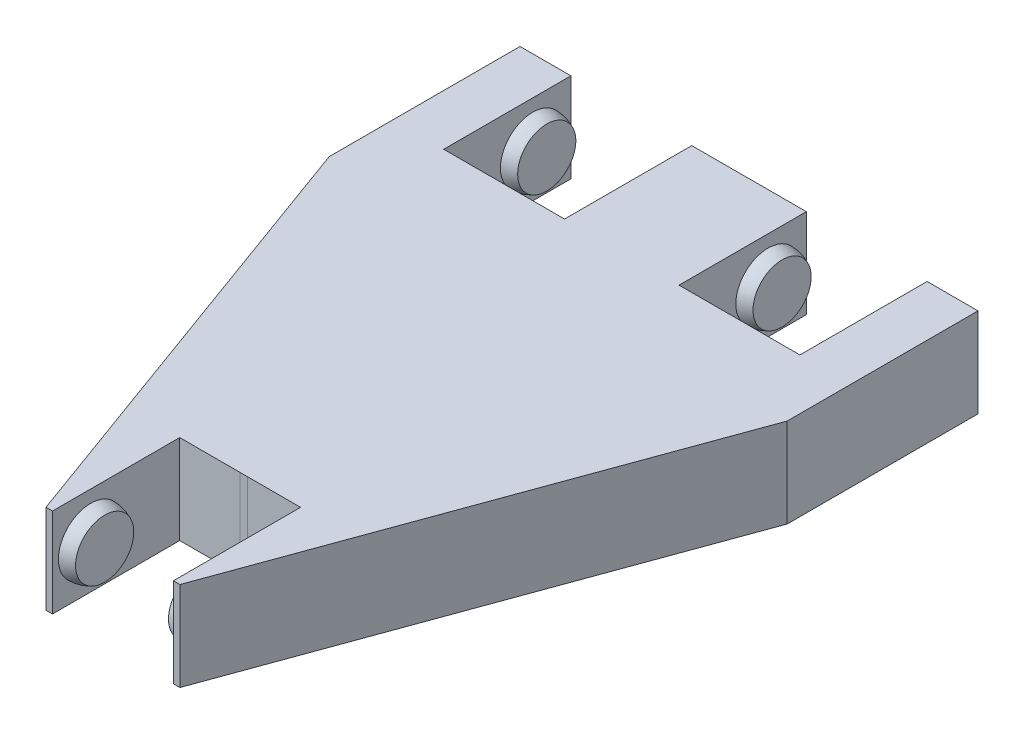
SolidWorks part; units mm, degrees
material "PBT General Purpose"
ref_plane "Front Plane" through (0, 0, 0) normal (0, 0, 1) x (1, 0, 0)
ref_plane "Top Plane" through (0, 0, 0) normal (0, 1, 0) x (1, 0, 0)
ref_plane "Right Plane" through (0, 0, 0) normal (1, 0, 0) x (0, 0, -1)
sketch "Sketch1" plane through (0, 0, 0) normal (0, 1, 0) x (1, 0, 0)
  line L1 (-36, 50) -> (36, 50)
  line L2 (-36, 50) -> (-36, -50)
  line L3 (-36, -50) -> (36, -50)
  line L4 (36, 50) -> (36, -50)
  line L5 (-36, 50) -> (36, -50) construction
  line L6 (-36, -50) -> (36, 50) construction
  line L7 (-28, 50) -> (-9, 50)
  line L8 (-28, 50) -> (-28, 30)
  line L9 (-28, 30) -> (-9, 30)
  line L10 (-9, 50) -> (-9, 30)
  line L11 (9, 50) -> (28, 50)
  line L12 (9, 50) -> (9, 30)
  line L13 (9, 30) -> (28, 30)
  line L14 (28, 50) -> (28, 30)
  line L15 (-9.5, -30) -> (9.5, -30)
  line L16 (-9.5, -30) -> (-9.5, -50)
  line L17 (-9.5, -50) -> (9.5, -50)
  line L18 (9.5, -30) -> (9.5, -50)
  point P0 (0, 0)
  point P14 (-9.5, -40)
  dimension "D1" = 100
  dimension "D2" = 72
  dimension "D3" = 20
  dimension "D4" = 19
  dimension "D5" = 19
  dimension "D6" = 20
  dimension "D7" = 18
  dimension "D8" = 8
  dimension "D9" = 19
  dimension "D10" = 20
  dimension "D11" = 26.5
extrude "Boss-Extrude1" add sketch "Sketch1" along normal blind 14.0278 contours L15 L18 L3 L4 L1 L14 L13 L12 L10 L9 L8 L2 L16
chamfer "Chamfer1" distance 70 angle 20 1 edges at (36, 7.0139, 50)
chamfer "Chamfer2" distance 70 angle 20 1 edges at (-36, 7.0139, 50)
sketch "Sketch2" plane through (-9.5, 0, 0) normal (1, 0, 0) x (0, 0, -1)
  line L2 (-30, 0) -> (-50, 0) construction
  line L3 (-50, 14.0278) -> (-50, 0) construction
  circle A0 centre (-44, 7) radius 5.075
  dimension "D3" = 10.15
  dimension "D1" = 7
  dimension "D2" = 6
sketch "Sketch4" plane through (-9.5, 0, 0) normal (1, 0, 0) x (0, 0, -1)
  line L0 (-49.075, 7) -> (-38.925, 7)
  arc A0 (-38.925, 7) -> (-49.075, 7) centre (-44, 7) ccw
  circle A1 centre (-44, 7) radius 5.075 construction
revolve "Revolve1" add sketch "Sketch4" angle 180 about L0
sketch "Sketch5" plane through (0, 0, 50) normal (0, 0, 1) x (1, 0, 0)
  line L0 (-9.5, 1.925) -> (-9.5, 12.075) construction
  line L1 (-7.3, 13.519) -> (-3.9276, 13.519)
  line L2 (-7.3, 13.519) -> (-7.3, 1.5195)
  line L3 (-7.3, 1.5195) -> (-3.9276, 1.5195)
  line L4 (-3.9276, 13.519) -> (-3.9276, 1.5195)
  dimension "D1" = 2.2
extrude "Cut-Extrude1" cut sketch "Sketch5" against normal blind 12
sketch "Sketch8" plane through (-28, 0, 0) normal (1, 0, 0) x (0, 0, -1)
  line L0 (38.925, 7) -> (49.075, 7)
  line L1 (50, 14.0278) -> (50, 0) construction
  line L2 (50, 0) -> (30, 0) construction
  arc A0 (38.925, 7) -> (49.075, 7) centre (44, 7) cw
  dimension "D1" = 5.075
  dimension "D2" = 6
  dimension "D3" = 7
revolve "Revolve2" add sketch "Sketch8" angle 180 about L0
sketch "Sketch10" plane through (0, 0, -50) normal (0, 0, -1) x (-1, 0, 0)
  line L0 (9, 14.0278) -> (-9, 14.0278) construction
  line L1 (0, 14.0278) -> (-9, 14.0278)
  line L2 (0, 14.0278) -> (0, 0)
  line L3 (0, 0) -> (-9, 0)
  line L4 (-9, 14.0278) -> (-9, 0)
extrude "Boss-Extrude2" add sketch "Sketch10" along normal blind 0.01
mirror "Mirror2" about plane through (0, 14.0278, -50.01) normal (1, 0, 0) of "Revolve2"
sketch "Sketch11" plane through (0, 0, 30) normal (0, 0, 1) x (1, 0, 0)
  line L0 (-9.5, 14.0278) -> (9.5, 14.0278) construction
  line L1 (0, 0) -> (1.1735, 0)
  line L2 (0, 0) -> (0, 14.0278)
  line L3 (0, 14.0278) -> (1.1735, 14.0278)
  line L4 (1.1735, 0) -> (1.1735, 14.0278)
extrude "Boss-Extrude3" add sketch "Sketch11" along normal blind 0.01
mirror "Mirror4" about plane through (0, 0, 30.01) normal (1, 0, 0) of "Revolve1"
sketch "Sketch12" plane through (0, 0, 50) normal (0, 0, 1) x (1, 0, 0)
  line L0 (9.5, 14.0278) -> (9.5, 0) construction
  line L1 (3.7027, 12.7379) -> (7.3, 12.7379)
  line L2 (3.7027, 12.7379) -> (3.7027, 1.3925)
  line L3 (3.7027, 1.3925) -> (7.3, 1.3925)
  line L4 (7.3, 12.7379) -> (7.3, 1.3925)
  dimension "D1" = 2.2
extrude "Cut-Extrude2" cut sketch "Sketch12" against normal blind 12
sketch "Sketch13" plane through (0, 0, -30) normal (0, 0, -1) x (-1, 0, 0)
  line L0 (-9, 0) -> (-28, 0) construction
  line L1 (-18.5, 0) -> (-16.6932, 0)
  line L2 (-18.5, 0) -> (-18.5, 14.0278)
  line L3 (-18.5, 14.0278) -> (-16.6932, 14.0278)
  line L4 (-16.6932, 0) -> (-16.6932, 14.0278)
  line L5 (-9, 14.0278) -> (-28, 14.0278) construction
extrude "Boss-Extrude4" add sketch "Sketch13" along normal blind 0.01
mirror "Mirror5" about plane through (18.5, 0, -30.01) normal (-1, 0, 0) of "Mirror2"
mirror "Mirror6" about plane through (0, 14.0278, -50.01) normal (1, 0, 0) of "Mirror5"
sketch "Sketch14" plane through (0, 0, -50) normal (0, 0, -1) x (-1, 0, 0)
  line L0 (-9, 12.075) -> (-9, 1.925) construction
  line L1 (-25.8, 12.7501) -> (-11.2, 12.7501)
  line L2 (-25.8, 12.7501) -> (-25.8, 1.2155)
  line L3 (-25.8, 1.2155) -> (-11.2, 1.2155)
  line L4 (-11.2, 12.7501) -> (-11.2, 1.2155)
  line L5 (11.2, 12.7501) -> (25.8, 12.7501)
  line L6 (11.2, 12.7501) -> (11.2, 1.2155)
  line L7 (11.2, 1.2155) -> (25.8, 1.2155)
  line L8 (25.8, 12.7501) -> (25.8, 1.2155)
  line L9 (-28, 14.0278) -> (-28, 0) construction
  line L10 (9, 14.0278) -> (9, 0) construction
  line L11 (28, 14.0278) -> (28, 0) construction
  dimension "D1" = 2.2
  dimension "D2" = 2.2
  dimension "D3" = 2.2
  dimension "D4" = 2.2
extrude "Cut-Extrude3" cut sketch "Sketch14" against normal blind 12
